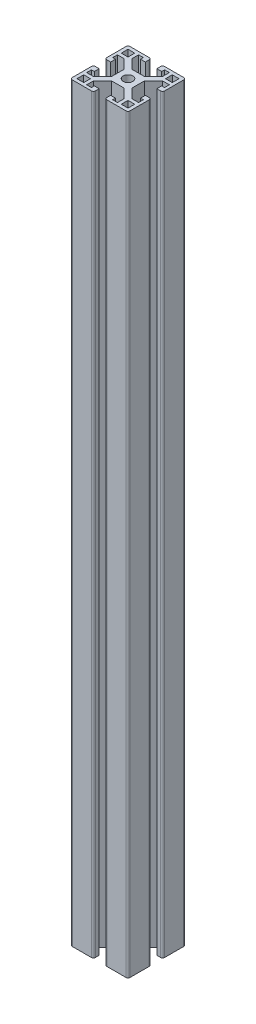
SolidWorks part; units mm, degrees
material "1060 Alloy"
ref_plane "Front Plane" through (0, 0, 0) normal (0, 0, 1) x (1, 0, 0)
ref_plane "Top Plane" through (0, 0, 0) normal (0, 1, 0) x (1, 0, 0)
ref_plane "Right Plane" through (0, 0, 0) normal (1, 0, 0) x (0, 0, -1)
sketch "Sketch1" plane through (0, 0, 0) normal (0, 1, 0) x (1, 0, 0)
  line L0 (-15, 7.5) -> (-15, -4.5)
  line L1 (-15, 7.5) -> (15, 7.5) construction
  line L2 (-15, 7.5) -> (-15, -7.5) construction
  line L3 (-15, -7.5) -> (15, -7.5) construction
  line L4 (15, 7.5) -> (15, -7.5) construction
  line L5 (0, -7.5) -> (0, 7.5) construction
  line L6 (-15, 0) -> (15, 0) construction
  line L7 (-15, 7.5) -> (-3, 7.5)
  line L8 (-15, -4.5) -> (-12, -4.5)
  line L9 (-12, -4.5) -> (-12, -2)
  line L10 (-12, -2) -> (-13.5, -2)
  line L11 (-13.5, -2) -> (-13.5, 0.5)
  line L12 (-13.5, 0.5) -> (-10, 0.5)
  line L13 (-5.25, -2.25) -> (5.25, -2.25) construction
  line L14 (-5.25, -2.25) -> (-5.25, -12.75) construction
  line L15 (-5.25, -12.75) -> (5.25, -12.75) construction
  line L16 (5.25, -2.25) -> (5.25, -12.75) construction
  line L17 (0, -12.75) -> (0, -2.25) construction
  line L18 (-5.25, -7.5) -> (5.25, -7.5) construction
  line L19 (-2.5857, -4.9143) -> (-15, 7.5) construction
  line L20 (-10, 0.5) -> (-5.25, -4.25)
  line L21 (-8, 2.5) -> (-3.25, -2.25)
  line L22 (-3, 7.5) -> (-3, 4.5)
  line L23 (-3, 4.5) -> (-5.5, 4.5)
  line L24 (-5.5, 4.5) -> (-5.5, 6)
  line L25 (-5.5, 6) -> (-8, 6)
  line L26 (-8, 6) -> (-8, 2.5)
  line L27 (5.5, 4.5) -> (5.5, 6)
  line L28 (-13.25, 5.75) -> (-9.75, 5.75)
  line L29 (-13.25, 5.75) -> (-13.25, 2.25)
  line L30 (-13.25, 2.25) -> (-9.75, 2.25)
  line L31 (-9.75, 5.75) -> (-9.75, 2.25)
  line L32 (-11.5, 2.25) -> (-11.5, 5.75) construction
  line L33 (-13.25, 4) -> (-9.75, 4) construction
  line L34 (13.25, 2.25) -> (9.75, 2.25)
  line L35 (13.25, 5.75) -> (13.25, 2.25)
  line L36 (13.25, 5.75) -> (9.75, 5.75)
  line L37 (9.75, 5.75) -> (9.75, 2.25)
  line L38 (3, 4.5) -> (5.5, 4.5)
  line L39 (3, 7.5) -> (3, 4.5)
  line L40 (5.5, 6) -> (8, 6)
  line L41 (8, 6) -> (8, 2.5)
  line L42 (15, 7.5) -> (3, 7.5)
  line L43 (13.5, 0.5) -> (10, 0.5)
  line L44 (13.5, -2) -> (13.5, 0.5)
  line L45 (12, -2) -> (13.5, -2)
  line L46 (15, 7.5) -> (15, -4.5)
  line L47 (15, -4.5) -> (12, -4.5)
  line L48 (12, -4.5) -> (12, -2)
  line L49 (8, 2.5) -> (3.25, -2.25)
  line L50 (10, 0.5) -> (5.25, -4.25)
  line L51 (-5.25, -4.25) -> (-5.25, -10.75)
  line L52 (-3.25, -2.25) -> (3.25, -2.25)
  line L53 (5.25, -4.25) -> (5.25, -10.75)
  line L54 (15, -22.5) -> (15, -10.5)
  line L55 (15, -10.5) -> (12, -10.5)
  line L56 (12, -10.5) -> (12, -13)
  line L57 (12, -13) -> (13.5, -13)
  line L58 (13.5, -13) -> (13.5, -15.5)
  line L59 (13.5, -15.5) -> (10, -15.5)
  line L60 (13.25, -17.25) -> (9.75, -17.25)
  line L61 (13.25, -20.75) -> (13.25, -17.25)
  line L62 (13.25, -20.75) -> (9.75, -20.75)
  line L63 (9.75, -20.75) -> (9.75, -17.25)
  line L64 (8, -21) -> (8, -17.5)
  line L65 (5.5, -21) -> (8, -21)
  line L66 (5.5, -19.5) -> (5.5, -21)
  line L67 (15, -22.5) -> (3, -22.5)
  line L68 (3, -22.5) -> (3, -19.5)
  line L69 (3, -19.5) -> (5.5, -19.5)
  line L70 (10, -15.5) -> (5.25, -10.75)
  line L71 (8, -17.5) -> (3.25, -12.75)
  line L72 (-3, -22.5) -> (-3, -19.5)
  line L73 (-3, -19.5) -> (-5.5, -19.5)
  line L74 (-5.5, -19.5) -> (-5.5, -21)
  line L75 (-5.5, -21) -> (-8, -21)
  line L76 (-8, -21) -> (-8, -17.5)
  line L77 (-15, -22.5) -> (-3, -22.5)
  line L78 (-9.75, -20.75) -> (-9.75, -17.25)
  line L79 (-13.25, -20.75) -> (-9.75, -20.75)
  line L80 (-13.25, -20.75) -> (-13.25, -17.25)
  line L81 (-13.25, -17.25) -> (-9.75, -17.25)
  line L82 (-13.5, -15.5) -> (-10, -15.5)
  line L83 (-13.5, -13) -> (-13.5, -15.5)
  line L84 (-12, -13) -> (-13.5, -13)
  line L85 (-15, -22.5) -> (-15, -10.5)
  line L86 (-15, -10.5) -> (-12, -10.5)
  line L87 (-12, -10.5) -> (-12, -13)
  line L88 (-3.25, -12.75) -> (3.25, -12.75)
  line L89 (-8, -17.5) -> (-3.25, -12.75)
  line L90 (-10, -15.5) -> (-5.25, -10.75)
  circle A0 centre (0, -7.5) radius 2.5
  point P0 (0, 0)
  point P18 (-11.5, 4)
  dimension "D7" = 1.5
  dimension "D19" = 5
  dimension "D1" = 30
  dimension "D2" = 15
  dimension "D3" = 12
  dimension "D4" = 12
  dimension "D5" = 3
  dimension "D6" = 2.5
  dimension "D8" = 2.5
  dimension "D9" = 10.5
  dimension "D10" = 3.5
  dimension "D11" = 45
  dimension "D12" = 3
  dimension "D13" = 2.5
  dimension "D14" = 1.5
  dimension "D15" = 2.5
  dimension "D16" = 3.5
  dimension "D17" = 3.5
  dimension "D18" = 3.5
extrude "Boss-Extrude1" add sketch "Sketch1" against normal blind 390
fillet "Fillet1" radius 1 12 edges at (-3, -195, -7.5) (-15, -195, -7.5) (-15, -195, 4.5) (-15, -195, 10.5) (3, -195, -7.5) (15, -195, -7.5) (15, -195, 4.5) (15, -195, 10.5) (3, -195, 22.5) (15, -195, 22.5) (-3, -195, 22.5) (-15, -195, 22.5)
